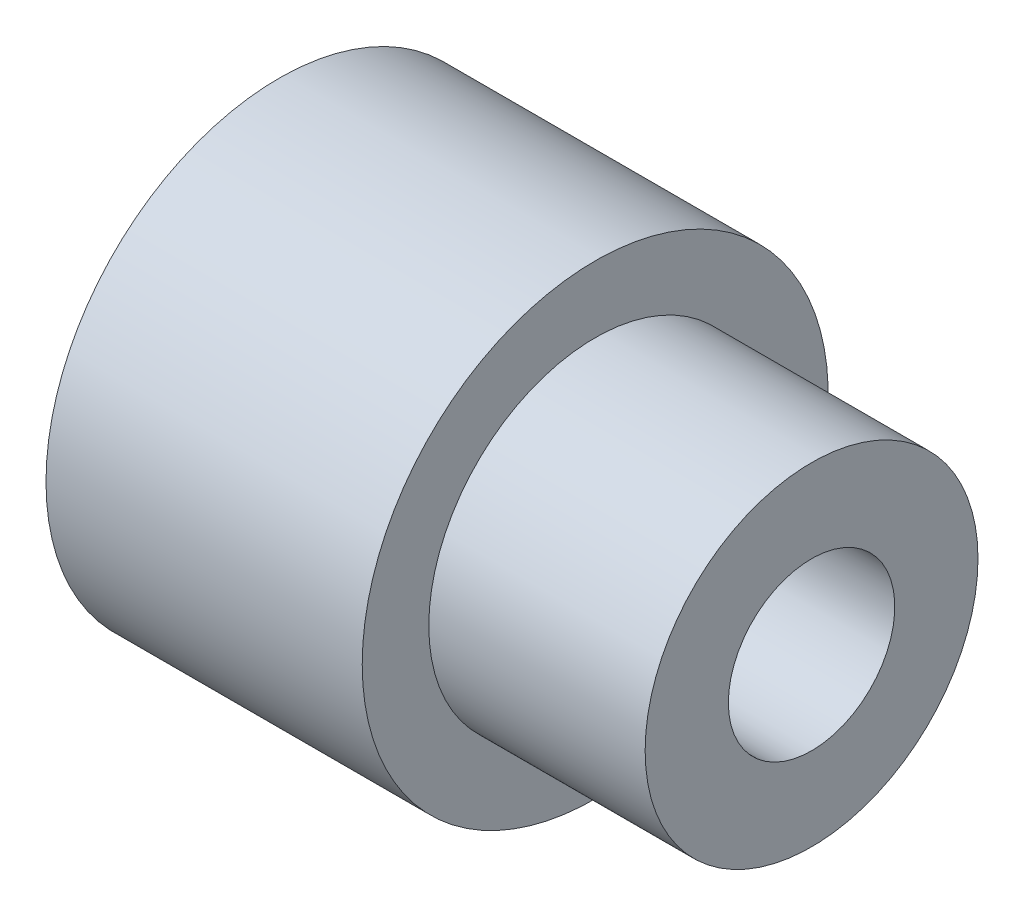
SolidWorks part; units mm, degrees
material "AISI 1035 Steel (SS)"
ref_plane "Front Plane" through (0, 0, 0) normal (0, 0, 1) x (1, 0, 0)
ref_plane "Top Plane" through (0, 0, 0) normal (0, 1, 0) x (1, 0, 0)
ref_plane "Right Plane" through (0, 0, 0) normal (1, 0, 0) x (0, 0, -1)
sketch "Sketch1" plane through (0, 0, 0) normal (0, 0, 1) x (1, 0, 0)
  line L0 (-24.6126, 0) -> (27.845, 0) construction
  line L1 (-16, 11) -> (-16, 14)
  line L2 (-16, 14) -> (3, 14)
  line L3 (3, 14) -> (3, 10)
  line L4 (3, 10) -> (16, 10)
  line L5 (16, 10) -> (16, 5)
  line L6 (16, 5) -> (0, 5)
  line L7 (0, 5) -> (0, 9)
  line L8 (0, 9) -> (-10, 9)
  line L9 (-10, 9) -> (-10, 11)
  line L10 (-10, 11) -> (-16, 11)
  dimension "D1" = 14
  dimension "D2" = 11
  dimension "D3" = 9
  dimension "D4" = 5
  dimension "D5" = 13
  dimension "D6" = 19
  dimension "D7" = 6
  dimension "D8" = 10
  dimension "D9" = 10
revolve "Revolve1" add sketch "Sketch1" angle 360 about L0
